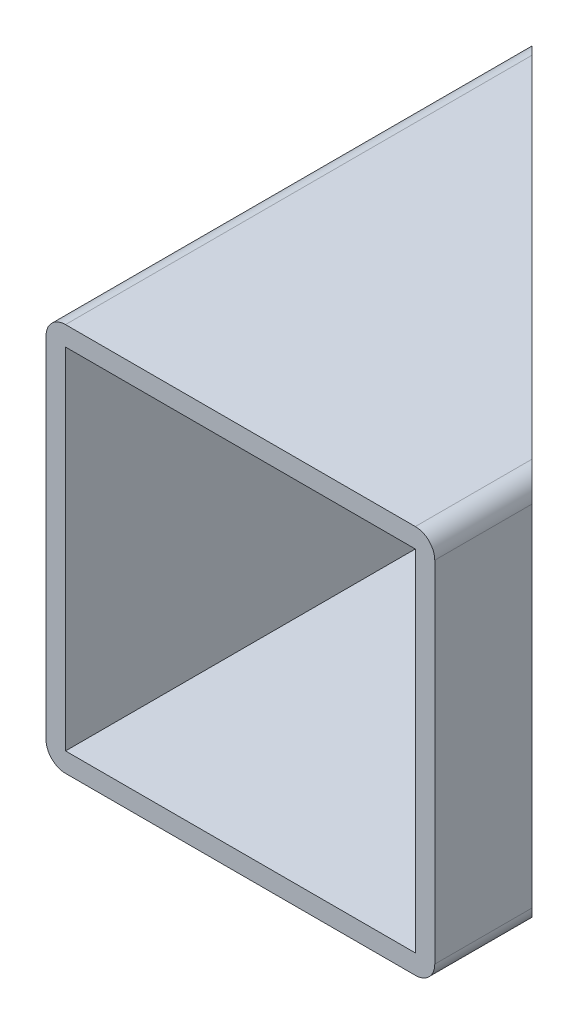
SolidWorks part; units mm, degrees
material "1.4305 (X8CrNiS18-9)"
ref_plane "Ön Düzlem" through (0, 0, 0) normal (0, 0, 1) x (1, 0, 0)
ref_plane "Üst Düzlem" through (0, 0, 0) normal (0, 1, 0) x (1, 0, 0)
ref_plane "Sağ Düzlem" through (0, 0, 0) normal (1, 0, 0) x (0, 0, -1)
sketch "Çizim1" plane through (0, 0, 0) normal (0, 0, 1) x (1, 0, 0)
  line L0 (-36, 36) -> (-36, -36)
  line L1 (-36, 40) -> (36, 40)
  line L2 (-40, 36) -> (-40, -36)
  line L3 (-36, -40) -> (36, -40)
  line L4 (40, 36) -> (40, -36)
  line L5 (-40, 40) -> (40, -40) construction
  line L6 (-40, -40) -> (40, 40) construction
  line L7 (-36, -36) -> (36, -36)
  line L8 (36, 36) -> (36, -36)
  line L9 (-36, 36) -> (36, 36)
  arc A0 (40, -36) -> (36, -40) centre (36, -36) cw
  arc A1 (36, 40) -> (40, 36) centre (36, 36) cw
  arc A2 (-36, 40) -> (-40, 36) centre (-36, 36) ccw
  arc A3 (-40, -36) -> (-36, -40) centre (-36, -36) ccw
  arc A4 (-36, -36) -> (-36, -36) centre (-36, -36) ccw
  arc A5 (36, -36) -> (36, -36) centre (36, -36) cw
  arc A6 (36, 36) -> (36, 36) centre (36, 36) cw
  arc A7 (-36, 36) -> (-36, 36) centre (-36, 36) ccw
  point P0 (0, 0)
  dimension "D3" = 4
  dimension "D1" = 80
  dimension "D2" = 80
  dimension "D4" = 4
extrude "Yükseklik-Ekstrüzyon1" add sketch "Çizim1" along normal blind 100
sketch "Çizim4" plane through (0, 0, 0) normal (0, 1, 0) x (1, 0, 0)
  line L0 (-40, 0) -> (40, -80)
  line L1 (40, -100) -> (40, 0) construction
  line L2 (40, -80) -> (40, 0)
  line L3 (40, 0) -> (-40, 0)
  dimension "D1" = 45
extrude "Kes-Ekstrüzyon2" cut sketch "Çizim4" against normal blind 90 and the other way blind 67
